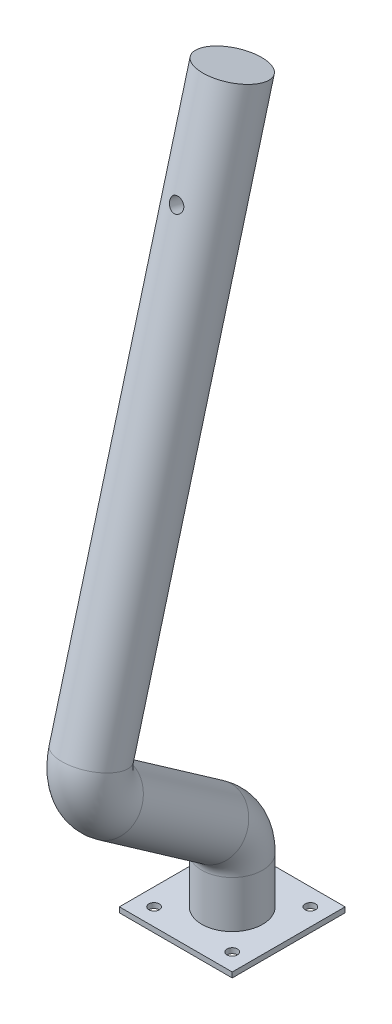
SolidWorks part; units mm, degrees
ref_plane "前视基准面" through (0, 0, 0) normal (0, 0, 1) x (1, 0, 0)
ref_plane "上视基准面" through (0, 0, 0) normal (0, 1, 0) x (1, 0, 0)
ref_plane "右视基准面" through (0, 0, 0) normal (1, 0, 0) x (0, 0, -1)
sketch "草图1" plane through (0, 0, 0) normal (0, 1, 0) x (1, 0, 0)
  line L1 (-32.5, -32.5) -> (32.5, -32.5)
  line L2 (-32.5, -32.5) -> (-32.5, 32.5)
  line L3 (-32.5, 32.5) -> (32.5, 32.5)
  line L4 (32.5, -32.5) -> (32.5, 32.5)
  line L5 (-32.5, -32.5) -> (32.5, 32.5) construction
  line L6 (-32.5, 32.5) -> (32.5, -32.5) construction
  circle A0 centre (22.5, -22.5) radius 3
  circle A1 centre (-22.5, -22.5) radius 3
  circle A2 centre (-22.5, 22.5) radius 3
  circle A3 centre (22.5, 22.5) radius 3
  point P0 (0, 0)
  point P17 (0, 0)
  dimension "D3" = 6
  dimension "D1" = 65
  dimension "D2" = 65
  dimension "D4" = 10
  dimension "D5" = 4
extrude "凸台-拉伸1" add sketch "草图1" along normal blind 3
sketch "草图2" plane through (0, 0, 0) normal (1, 0, 0) x (0, 0, -1)
  line L0 (0, 3) -> (0, 29.9858)
  line L1 (-32.5, 3) -> (32.5, 3) construction
  line L2 (-10.6606, 50.4646) -> (-71.3495, 92.9594)
  line L3 (-81.1582, 119.9087) -> (0, 422.7953)
  arc A0 (-71.3495, 92.9594) -> (-81.1582, 119.9087) centre (-57.0101, 113.4382) cw
  arc A1 (0, 29.9858) -> (-10.6606, 50.4646) centre (-25, 29.9858) ccw
  point P6 (-49.2952, 144.3636)
  point P8 (0, 0)
  point P9 (0, 267.2698)
  point P10 (0, 0)
  point P13 (-85.6889, 103)
  point P16 (0, 43)
  dimension "D5" = 25
  dimension "D1" = 40
  dimension "D2" = 125
  dimension "D3" = 110
  dimension "D4" = 60
sweep "扫描1" add path "草图2" circular profile diameter 35 parameters "D3"=35
ref_plane "基准面1" through (0, 28.3219, 105.6988) normal (0, -0.2588, -0.9659) x (0, 0.9659, -0.2588)
sketch "草图31" plane through (0, 28.3219, 105.6988) normal (0, -0.2588, -0.9659) x (0, 0.9659, -0.2588)
  line L0 (94.8176, 0) -> (408.3889, 0) construction
  circle A0 centre (348.3889, 0) radius 4
  point P8 (0, 0)
  point P9 (0, 0)
  point P10 (227.7674, 0)
  dimension "D1" = 8
  dimension "D6" = 60
extrude "切除-拉伸1" cut sketch "草图31" against normal blind 50
